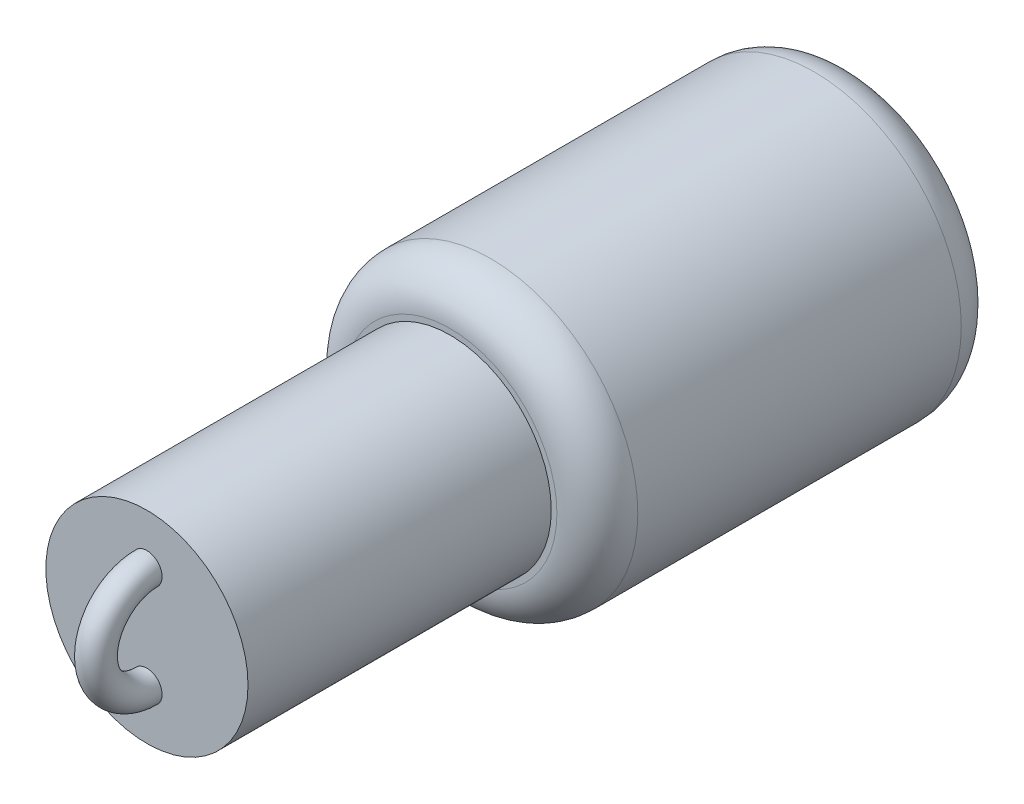
SolidWorks part; units mm, degrees
ref_plane "Front Plane" through (0, 0, 0) normal (0, 0, 1) x (1, 0, 0)
ref_plane "Top Plane" through (0, 0, 0) normal (0, 1, 0) x (1, 0, 0)
ref_plane "Right Plane" through (0, 0, 0) normal (1, 0, 0) x (0, 0, -1)
sketch "Sketch1" plane through (0, 0, 0) normal (0, 0, 1) x (1, 0, 0)
  circle A0 centre (0, 0) radius 7.28
extrude "Boss-Extrude1" add sketch "Sketch1" along normal blind 20
fillet "Fillet1" radius 2 2 edges at (7.28, 0, 20) (7.28, 0, 0)
sketch "Sketch2" plane through (0, 0, 20) normal (0, 0, 1) x (1, 0, 0)
  circle A0 centre (0, 0) radius 5
extrude "Boss-Extrude2" add sketch "Sketch2" along normal blind 15
sketch "Sketch4" plane through (0, 0, 35) normal (0, 0, 1) x (1, 0, 0)
  line L0 (-4.4664, 0) -> (4.4664, 0)
  circle A0 centre (0, 2.5195) radius 0.75
revolve "Revolve1" add sketch "Sketch4" angle 200 about L0
